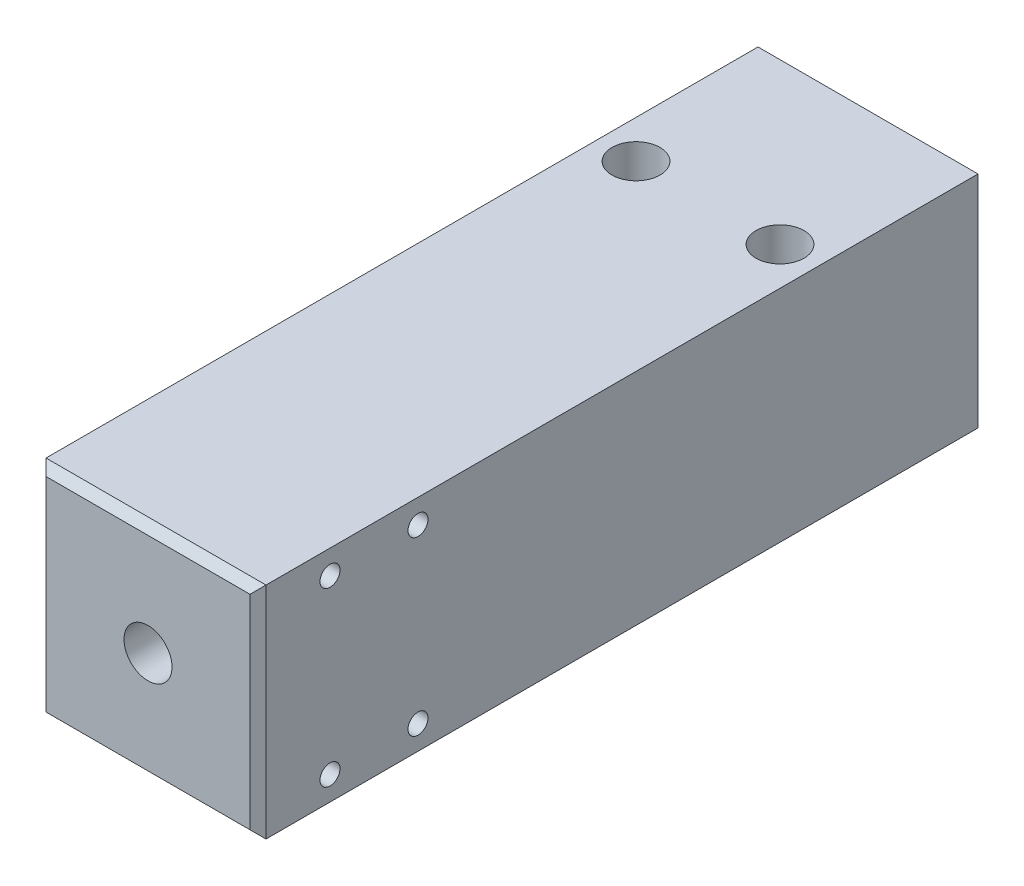
SolidWorks part; units mm, degrees
ref_plane "Alzado" through (0, 0, 0) normal (0, 0, 1) x (1, 0, 0)
ref_plane "Planta" through (0, 0, 0) normal (0, 1, 0) x (1, 0, 0)
ref_plane "Vista lateral" through (0, 0, 0) normal (1, 0, 0) x (0, 0, -1)
sketch "Croquis1" plane through (0, 0, 0) normal (0, 0, 1) x (1, 0, 0)
  line L1 (-27.5, 27.5) -> (27.5, 27.5)
  line L2 (-27.5, 27.5) -> (-27.5, -27.5)
  line L3 (-27.5, -27.5) -> (27.5, -27.5)
  line L4 (27.5, 27.5) -> (27.5, -27.5)
  line L5 (-27.5, 27.5) -> (27.5, -27.5) construction
  line L6 (-27.5, -27.5) -> (27.5, 27.5) construction
  point P0 (0, 0)
  dimension "D1" = 55
  dimension "D2" = 55
extrude "Saliente-Extruir1" add sketch "Croquis1" against normal blind 180
sketch "Croquis2" plane through (0, 0, 0) normal (0, 0, 1) x (1, 0, 0)
  circle A0 centre (0, 0) radius 6
  dimension "D1" = 12
extrude "Cortar-Extruir1" cut sketch "Croquis2" against normal blind 30
sketch "Croquis3" plane through (0, 0, -180) normal (0, 0, -1) x (-1, 0, 0)
  circle A0 centre (18, 18) radius 4
  circle A1 centre (-18, 18) radius 4
  circle A2 centre (-18, -18) radius 4
  circle A3 centre (18, -18) radius 4
  dimension "D2" = 18
  dimension "D9" = 8
  dimension "D10" = 8
  dimension "D11" = 8
  dimension "D12" = 8
  dimension "D1" = 18
  dimension "D3" = 18
  dimension "D4" = 18
  dimension "D5" = 18
  dimension "D6" = 18
  dimension "D7" = 18
  dimension "D8" = 18
extrude "Cortar-Extruir2" cut sketch "Croquis3" against normal blind 25
sketch "Croquis4" plane through (27.5, 0, 0) normal (1, 0, 0) x (0, 0, -1)
  line L0 (0, -27.5) -> (0, 27.5) construction
  circle A0 centre (18, 21.5) radius 2.5
  circle A1 centre (40, 21.5) radius 2.5
  circle A2 centre (40, -21.5) radius 2.5
  circle A3 centre (18, -21.5) radius 2.5
  point P11 (0, 0)
  dimension "D1" = 21.5
  dimension "D2" = 18
  dimension "D3" = 18
  dimension "D7" = 22
  dimension "D8" = 22
  dimension "D9" = 5
  dimension "D10" = 5
  dimension "D11" = 5
  dimension "D12" = 5
  dimension "D4" = 21.5
  dimension "D5" = 21.5
  dimension "D6" = 21.5
extrude "Cortar-Extruir3" cut sketch "Croquis4" against normal blind 15
sketch "Croquis5" plane through (-27.5, 0, 0) normal (-1, 0, 0) x (0, 0, 1)
  line L0 (0, 27.5) -> (0, -27.5) construction
  circle A0 centre (-18, 21.5) radius 2.5
  circle A1 centre (-40, 21.5) radius 2.5
  circle A2 centre (-40, -21.5) radius 2.5
  circle A3 centre (-18, -21.5) radius 2.5
  dimension "D5" = 22
  dimension "D6" = 22
  dimension "D7" = 18
  dimension "D8" = 18
  dimension "D9" = 5
  dimension "D10" = 5
  dimension "D11" = 5
  dimension "D12" = 5
  dimension "D1" = 21.5
  dimension "D2" = 21.5
  dimension "D3" = 21.5
  dimension "D4" = 21.5
extrude "Cortar-Extruir4" cut sketch "Croquis5" against normal blind 15
sketch "Croquis6" plane through (0, 27.5, 0) normal (0, 1, 0) x (1, 0, 0)
  line L0 (27.5, 180) -> (-27.5, 180) construction
  circle A0 centre (-18, 140) radius 6
  circle A1 centre (18, 140) radius 6
  dimension "D1" = 40
  dimension "D2" = 40
  dimension "D3" = 18
  dimension "D5" = 12
  dimension "D6" = 12
  dimension "D4" = 18
extrude "Cortar-Extruir5" cut sketch "Croquis6" against normal blind 12
chamfer "Chaflán1" distance 2 angle 45 4 edges at (0, -27.5, 0) (-27.5, 0, 0) (27.5, 0, 0) (0, 27.5, 0)
